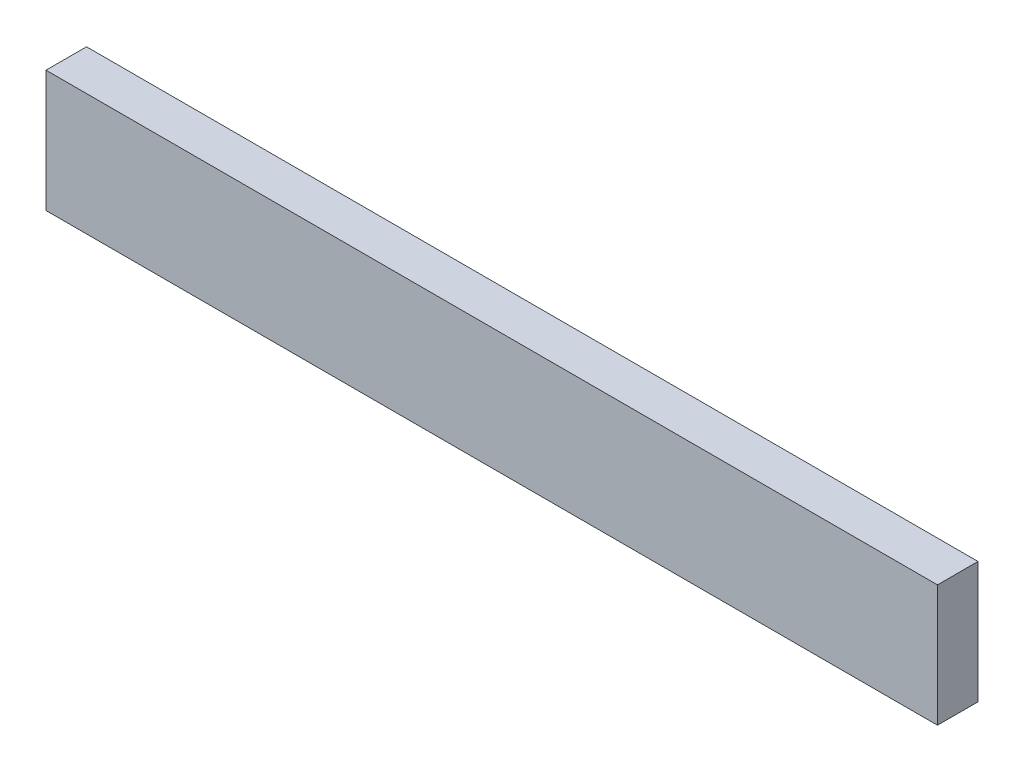
SolidWorks part; units mm, degrees
ref_plane "Plano frontal" through (0, 0, 0) normal (0, 0, 1) x (1, 0, 0)
ref_plane "Plano superior" through (0, 0, 0) normal (0, 1, 0) x (1, 0, 0)
ref_plane "Plano direito" through (0, 0, 0) normal (1, 0, 0) x (0, 0, -1)
sketch "Esboço1" plane through (0, 0, 0) normal (0, 0, 1) x (1, 0, 0)
  line L1 (-58.907, -13.195) -> (51.093, -13.195)
  line L2 (-58.907, -13.195) -> (-58.907, -28.195)
  line L3 (-58.907, -28.195) -> (51.093, -28.195)
  line L4 (51.093, -13.195) -> (51.093, -28.195)
extrude "Ressalto-extrusão1" add sketch "Esboço1" along normal blind 5
